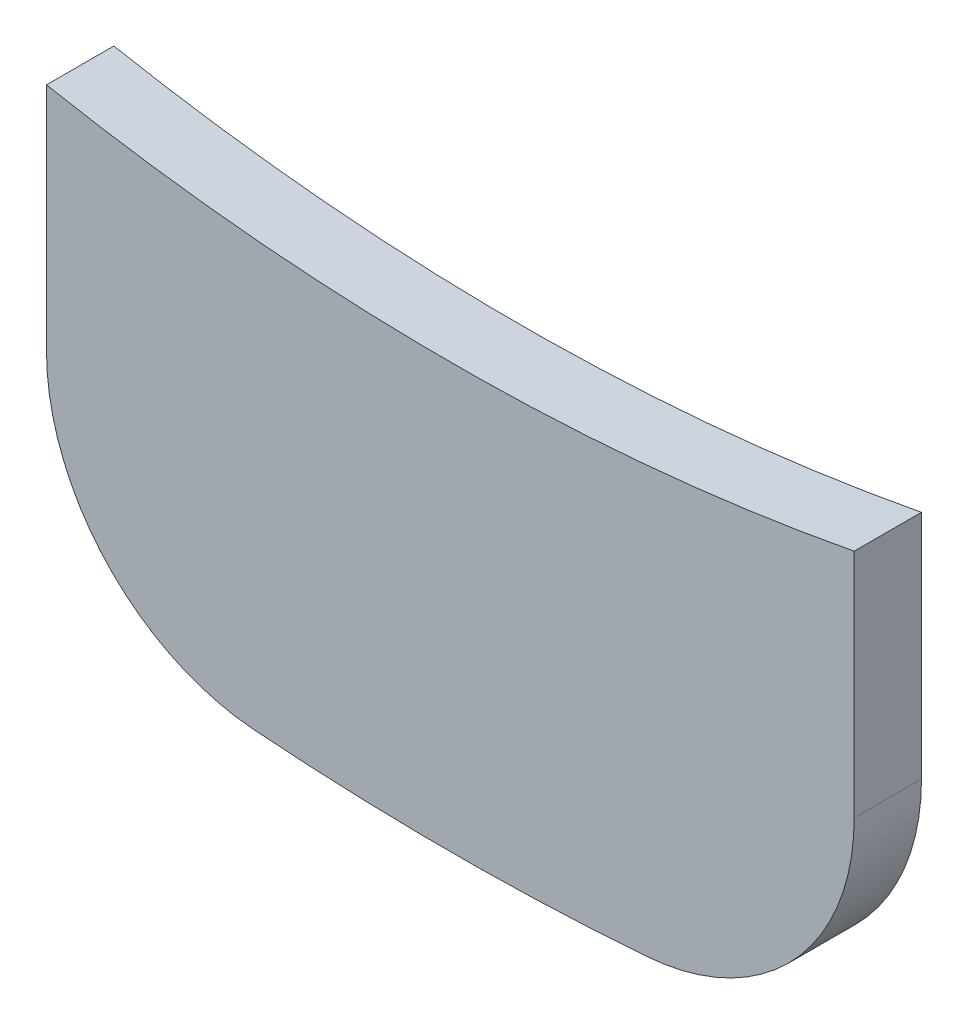
SolidWorks part; units mm, degrees
ref_plane "Front Plane" through (0, 0, 0) normal (0, 0, 1) x (1, 0, 0)
ref_plane "Top Plane" through (0, 0, 0) normal (0, 1, 0) x (1, 0, 0)
ref_plane "Right Plane" through (0, 0, 0) normal (1, 0, 0) x (0, 0, -1)
sketch "Sketch2" plane through (0, 0, 0) normal (0, 0, 1) x (1, 0, 0)
  line L3 (18, -104.6948) -> (18, -94.3992)
  line L5 (-18, -94.3992) -> (-18, -104.6948)
  arc A6 (-18, -104.6948) -> (-8.7619, -114.6657) centre (-8, -104.6948) ccw
  arc A7 (-8.7619, -114.6657) -> (8.7619, -114.6657) centre (0, 0) ccw
  arc A8 (8.7619, -114.6657) -> (17.1849, -108.6493) centre (8, -104.6948) ccw
  arc A9 (17.1849, -108.6493) -> (18, -104.6948) centre (8, -104.6948) ccw
  arc A10 (-18, -94.3992) -> (18, -94.3992) centre (0, 0) ccw
extrude "Boss-Extrude1" add sketch "Sketch2" along normal blind 3
